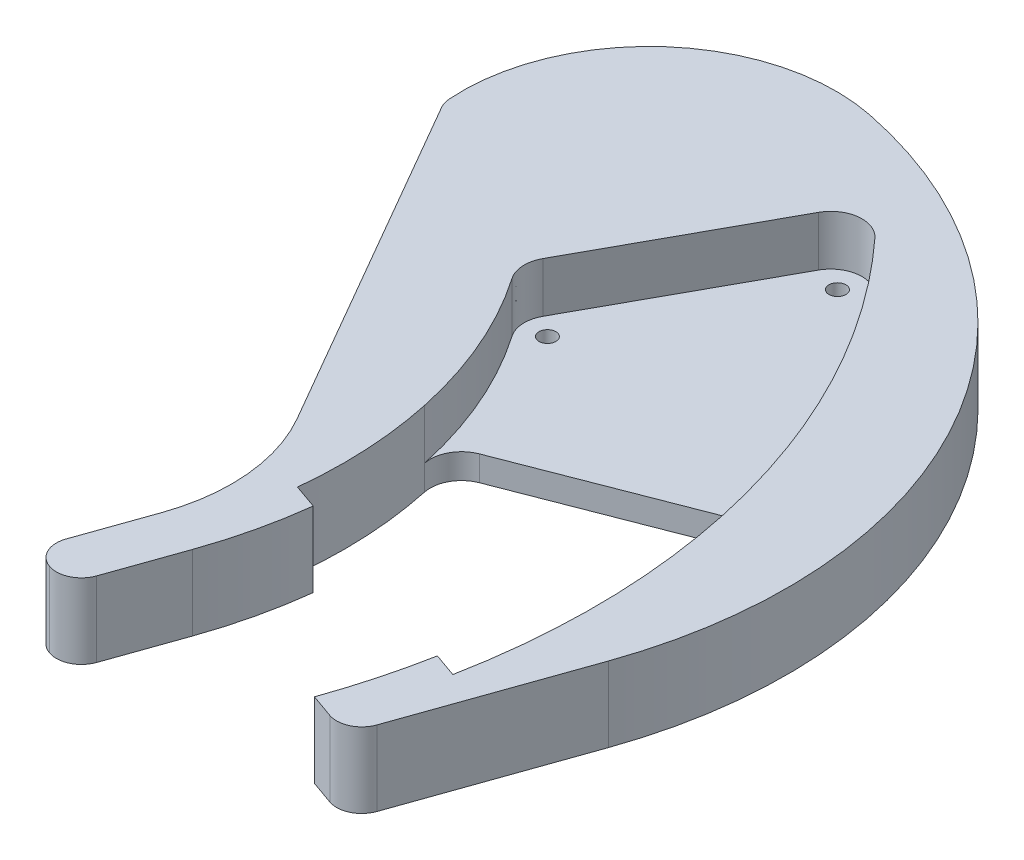
SolidWorks part; units mm, degrees
material "Pine"
ref_plane "Front Plane" through (0, 0, 0) normal (0, 0, 1) x (1, 0, 0)
ref_plane "Top Plane" through (0, 0, 0) normal (0, 1, 0) x (1, 0, 0)
ref_plane "Right Plane" through (0, 0, 0) normal (1, 0, 0) x (0, 0, -1)
sketch "Sketch1" plane through (0, 0, 0) normal (0, 1, 0) x (1, 0, 0)
  line L59 (-47.4532, 53.4043) -> (-98.2532, 141.3925)
  line L60 (0, 0) -> (27.9445, -9.8615)
  line L61 (0, 0) -> (-43.9505, 15.5099)
  line L62 (-1000, 0) -> (49000, 0) construction
  line L64 (27.9445, -9.8615) -> (72.8551, -25.7103) construction
  line L65 (72.8551, -25.7103) -> (88.7038, 19.2003) construction
  line L66 (27.9445, -9.8615) -> (-207.1917, -676.1663) construction
  line L67 (45.3803, 39.5461) -> (27.9445, -9.8615)
  line L68 (-43.9505, 15.5099) -> (-28.1017, 60.4205) construction
  line L69 (-88.861, 31.3587) -> (-86.5095, 38.0222) construction
  line L70 (53.7407, 188.0768) -> (-24.6782, 188.0768) construction
  line L71 (-43.9505, 15.5099) -> (-88.861, 31.3587) construction
  arc A0 (45.3803, 39.5461) -> (-41.5665, 192.8393) centre (-64.7226, 78.401) ccw
  arc A1 (-98.2532, 141.3925) -> (-41.5665, 192.8393) centre (-50.9898, 146.2689) cw
  arc A2 (-43.9505, 15.5099) -> (-47.4532, 53.4043) centre (-86.8603, 30.6526) ccw
  dimension "D5" = 4.7625
  dimension "D2" = 45.5033
  dimension "D11" = 37.8944
  dimension "D12" = 7.0663
  dimension "D8" = 52.3939
  dimension "D9" = 46.6069
  dimension "D4" = 19.438
  dimension "D7" = 116.7576
  dimension "D6" = 47.5143
  dimension "D10" = 29.6335
  dimension "D3" = 101.6
  dimension "D1" = 47.625
  dimension "D13" = 78.4189
extrude "Boss-Extrude1" add sketch "Sketch1" along normal blind 19.05
ref_plane "Plane1" through (-8.003, 0, -2.8242) normal (0.943, 0, 0.3328) x (0.3328, 0, -0.943)
sketch "Sketch2" plane through (0, 0, 0) normal (0, 1, 0) x (1, 0, 0)
  line L0 (-43.9505, 15.5099) -> (27.9445, -9.8615) construction
  point P2 (-8.003, 2.8242)
  point P3 (-8.003, 2.8242)
  line B0 (-29.2366, 81.4276) -> (15.5744, 98.7927)
  line B1 (11.6131, 92.147) -> (-21.6985, 79.2205)
  line B2 (-25.5648, 59.5252) -> (22.719, 42.4861)
  line B3 (28.6163, 16.8366) -> (22.5595, 18.974)
  line B4 (-26.1738, 36.1718) -> (-32.322, 38.3415)
  line B5 (-25.1489, 88.1192) -> (10.3796, 101.8872)
  line B6 (-51.3926, 119.7839) -> (-26.6046, 164.8774)
  line B7 (-44.0739, 123.2114) -> (-25.3, 157.3642)
  line B8 (-31.9553, 11.2769) -> (15.9493, -5.6285)
  line B9 (22.5595, 18.974) -> (-26.1738, 36.1718)
  arc B10 (-27.5994, 72.1341) -> (-28.8269, 77.6086) centre (-28.1238, 74.8914) ccw
  arc B11 (-29.2366, 81.4276) -> (-29.7842, 81.1914) centre (-26.3685, 74.0264) ccw
  arc B12 (17.8172, 99.3043) -> (15.5744, 98.7927) centre (18.4425, 91.3914) ccw
  arc B13 (18.8456, 95.8956) -> (20.3121, 90.5015) centre (19.3312, 93.1313) ccw
  arc B14 (13.6735, 91.1895) -> (20.9914, 87.3846) centre (19.3312, 93.1313) ccw
  arc B15 (-27.0229, 69.0118) -> (-22.587, 77.1552) centre (-28.1238, 74.8914) ccw
  arc B16 (20.3121, 90.5015) -> (18.8456, 95.8956) centre (19.3312, 93.1313) ccw
  arc B17 (28.6163, 16.8366) -> (26.1201, 93.4056) centre (-140.6727, 49.6428) ccw
  arc B18 (26.9496, 45.3998) -> (22.9664, 86.2145) centre (-140.6737, 49.643) ccw
  arc B19 (-28.827, 77.6085) -> (-27.5994, 72.1341) centre (-28.1238, 74.8914) ccw
  arc B20 (-27.6639, 62.1695) -> (-25.8173, 59.6267) centre (-24.5082, 62.5193) ccw
  arc B21 (-32.322, 38.3415) -> (-34.1314, 72.3702) centre (-140.6727, 49.6428) ccw
  arc B22 (10.3796, 101.8872) -> (14.8753, 112.2511) centre (7.5115, 109.2884) ccw
  arc B23 (-35.3684, 92.527) -> (-25.1489, 88.1192) centre (-28.017, 95.5204) ccw
  arc B24 (-43.0735, 110.8831) -> (-43.464, 121.0781) centre (-46.3902, 115.8611) ccw
  arc B25 (15.9493, -5.6285) -> (22.5595, 18.974) centre (-140.6729, 49.642) ccw
  arc B26 (-31.9553, 11.2769) -> (-26.1738, 36.1718) centre (-140.6725, 49.6436) ccw
  spline B27 degree 3 poles (17.8172, 99.3043) (18.2808, 99.3409) (18.7407, 99.3366) (19.6534, 99.2495) (20.1077, 99.1662) (21.0026, 98.9191) (21.4331, 98.7584) (22.0543, 98.4634) (22.2573, 98.356) (22.6549, 98.123) (22.8504, 97.9967) (23.4171, 97.5941) (23.7667, 97.2963) (24.2502, 96.807) (24.4045, 96.6367) (24.699, 96.2816) (24.84, 96.0958) (25.2347, 95.5249) (25.4616, 95.126) (25.8451, 94.2925) (26.0022, 93.8555) (26.1202, 93.4057) knots 0 0 0 0 0.125 0.125 0.25 0.25 0.375 0.375 0.4375 0.4375 0.5 0.5 0.625 0.625 0.6875 0.6875 0.75 0.75 0.875 0.875 1 1 1 1
  spline B28 degree 3 poles (-34.1313, 72.3702) (-34.3175, 73.2427) (-34.3554, 74.1214) (-34.1352, 75.8909) (-33.8828, 76.7344) (-33.0952, 78.3332) (-32.5797, 79.0482) (-31.6292, 79.9869) (-31.2886, 80.2706) (-30.5679, 80.7764) (-30.1868, 80.9994) (-29.7842, 81.1914) knots 0 0 0 0 0.25 0.25 0.5 0.5 0.75 0.75 0.875 0.875 1 1 1 1
  spline B29 degree 2 poles (-26.6046, 164.8774) (-26.1506, 165.7033) (-25.5154, 166.4003) (-24.879, 167.0987) (-24.0954, 167.6288) (-23.3138, 168.1575) (-22.4289, 168.4884) (-21.5475, 168.8181) (-20.6123, 168.9325) (-19.6749, 169.0473) (-18.7356, 168.9385) (-17.7973, 168.83) (-16.9097, 168.5037) (-16.0263, 168.179) (-15.2426, 167.656) (-14.4528, 167.129) (-13.8094, 166.4302) knots 0 0 0 0.125 0.125 0.25 0.25 0.375 0.375 0.5 0.5 0.625 0.625 0.75 0.75 0.875 0.875 1 1 1
  spline B30 degree 3 poles (26.1163, 93.4018) (24.3249, 100.238) (22.1302, 106.9013) (16.9621, 119.8936) (13.988, 126.2224) (9.777, 133.9217) (8.91, 135.4509) (7.1262, 138.488) (6.208, 139.9978) (3.3864, 144.4804) (1.4239, 147.3946) (-4.7015, 155.9203) (-9.1008, 161.3163) (-13.8094, 166.4302) knots 0 0 0 0 0.25 0.25 0.5 0.5 0.5625 0.5625 0.625 0.625 0.75 0.75 1 1 1 1
  spline B31 degree 3 poles (-13.3161, 158.7044) (-10.6959, 155.6457) (-8.187, 152.4937) (-4.3894, 147.3517) (-3.0295, 145.4278) (-0.3835, 141.5096) (0.9037, 139.513) (3.3926, 135.4673) (4.5925, 133.4211) (6.8969, 129.2936) (8.0024, 127.2107) (11.1817, 120.9021) (13.1195, 116.615) (14.8753, 112.2511) knots 0.074143 0.074143 0.074143 0.074143 0.222946 0.222946 0.309438 0.309438 0.395929 0.395929 0.48242 0.48242 0.568911 0.568911 0.741894 0.741894 0.741894 0.741894
  spline B32 degree 3 poles (-35.3684, 92.527) (-36.6307, 95.6269) (-38.0226, 98.6534) (-40.7885, 104.036) (-42.1249, 106.4194) (-43.5456, 108.7522) knots 0.447067 0.447067 0.447067 0.447067 0.670186 0.670186 0.854821 0.854821 0.854821 0.854821
  spline B33 degree 2 poles (-50.9715, 111.4537) (-51.5973, 112.3613) (-51.9523, 113.4056) (-52.3075, 114.4507) (-52.3641, 115.5542) (-52.4206, 116.6572) (-52.1734, 117.7348) (-51.9261, 118.8136) (-51.3926, 119.7839) knots 0 0 0 0.25 0.25 0.5 0.5 0.75 0.75 1 1 1
  spline B34 degree 3 poles (-50.9715, 111.4537) (-48.9588, 108.5346) (-47.0926, 105.5237) (-43.6539, 99.3178) (-42.0816, 96.1226) (-39.9504, 91.1875) (-39.2781, 89.5185) (-38.0214, 86.161) (-37.4355, 84.4688) (-36.3479, 81.058) (-35.8463, 79.3393) (-34.9276, 75.8754) (-34.5102, 74.1291) (-34.136, 72.3718) knots 0 0 0 0 0.25 0.25 0.5 0.5 0.625 0.625 0.75 0.75 0.875 0.875 1 1 1 1
sketch_block_instance "Ramp Geometry-1"
sketch_block "Ramp Geometry"
sketch "Sketch5" plane through (0, 19.05, 0) normal (0, 1, 0) x (1, 0, 0)
  line L1 (28.6163, 16.8366) -> (22.5595, 18.974) construction
  line L2 (-31.9553, 11.2769) -> (15.9493, -5.6285) construction
  line L3 (-26.1738, 36.1718) -> (-32.322, 38.3415) construction
  line L4 (-29.2366, 81.4276) -> (15.5744, 98.7927)
  line L5 (28.6163, 16.8366) -> (22.5595, 18.974)
  line L6 (-31.9553, 11.2769) -> (15.9493, -5.6285)
  line L7 (-26.1738, 36.1718) -> (-32.322, 38.3415)
  arc A2 (28.6163, 16.8366) -> (26.1201, 93.4056) centre (-140.6727, 49.6428) ccw construction
  arc A3 (15.9493, -5.6285) -> (22.5595, 18.974) centre (-140.6729, 49.642) ccw construction
  arc A4 (-31.9553, 11.2769) -> (-26.1738, 36.1718) centre (-140.6725, 49.6436) ccw construction
  arc A5 (-32.322, 38.3415) -> (-34.1314, 72.3702) centre (-140.6727, 49.6428) ccw construction
  arc A6 (-34.1314, 72.3702) -> (-29.2366, 81.4276) centre (-26.3759, 74.0303) cw
  arc A7 (26.1201, 93.4056) -> (15.5744, 98.7927) centre (18.4429, 91.3925) ccw
  arc A8 (28.6163, 16.8366) -> (26.1201, 93.4056) centre (-140.6727, 49.6428) ccw
  arc A9 (15.9493, -5.6285) -> (22.5595, 18.974) centre (-140.6729, 49.642) ccw
  arc A10 (-31.9553, 11.2769) -> (-26.1738, 36.1718) centre (-140.6725, 49.6436) ccw
  arc A11 (-32.322, 38.3415) -> (-34.1314, 72.3702) centre (-140.6727, 49.6428) ccw
  spline S2 degree 3 poles (17.8172, 99.3043) (18.2808, 99.3409) (18.7407, 99.3366) (19.6534, 99.2495) (20.1077, 99.1662) (21.0026, 98.9191) (21.4331, 98.7584) (22.0543, 98.4634) (22.2573, 98.356) (22.6549, 98.123) (22.8504, 97.9967) (23.4171, 97.5941) (23.7667, 97.2963) (24.2502, 96.807) (24.4045, 96.6367) (24.699, 96.2816) (24.84, 96.0958) (25.2347, 95.5249) (25.4616, 95.126) (25.8451, 94.2925) (26.0022, 93.8555) (26.1202, 93.4057) knots 0 0 0 0 0.125 0.125 0.25 0.25 0.375 0.375 0.4375 0.4375 0.5 0.5 0.625 0.625 0.6875 0.6875 0.75 0.75 0.875 0.875 1 1 1 1 construction
  spline S3 degree 3 poles (-34.1313, 72.3702) (-34.3175, 73.2427) (-34.3554, 74.1214) (-34.1352, 75.8909) (-33.8828, 76.7344) (-33.0952, 78.3332) (-32.5797, 79.0482) (-31.6292, 79.9869) (-31.2886, 80.2706) (-30.5679, 80.7764) (-30.1868, 80.9994) (-29.7842, 81.1914) knots 0 0 0 0 0.25 0.25 0.5 0.5 0.75 0.75 0.875 0.875 1 1 1 1 construction
extrude "Cut-Extrude1" cut sketch "Sketch5" against normal through all
sketch "Sketch6" plane through (0, 19.05, 0) normal (0, 1, 0) x (1, 0, 0)
  line L0 (-34.136, 72.3718) -> (26.1163, 93.4018)
  line L2 (-51.3926, 119.7839) -> (-26.6046, 164.8774) construction
  line L3 (-51.3926, 119.7839) -> (-26.6046, 164.8774)
  spline S0 degree 3 poles (-1429.6439, -1247.1312) (-221.2393, -482.3872) (103.2117, -96.9361) (16.9621, 119.8936) (13.988, 126.2224) (9.777, 133.9217) (8.91, 135.4509) (7.1262, 138.488) (6.208, 139.9978) (3.3864, 144.4804) (1.4239, 147.3946) (-186.5695, 409.0534) (-1027.0588, 71.2021) (-1932.3264, -325.7002) knots -7.844512 -7.844512 -7.844512 -7.844512 0.25 0.25 0.5 0.5 0.5625 0.5625 0.625 0.625 0.75 0.75 12.134027 12.134027 12.134027 12.134027 only from (26.1163, 93.4018) to (-13.8094, 166.4302) construction
  spline S1 degree 2 poles (1493.7423, -1132.5068) (-85.9486, 100.0778) (-25.5154, 166.4003) (-24.879, 167.0987) (-24.0954, 167.6288) (-23.3138, 168.1575) (-22.4289, 168.4884) (-21.5475, 168.8181) (-20.6123, 168.9325) (-19.6749, 169.0473) (-18.7356, 168.9385) (-17.7973, 168.83) (-16.9097, 168.5037) (-16.0263, 168.179) (-15.2426, 167.656) (59.3198, 117.902) (-1170.3473, -1463.6448) knots -11.768568 -11.768568 -11.768568 0.125 0.125 0.25 0.25 0.375 0.375 0.5 0.5 0.625 0.625 0.75 0.75 0.875 0.875 12.67723 12.67723 12.67723 only from (-26.6046, 164.8774) to (-13.8094, 166.4302) construction
  spline S2 degree 2 poles (1805.4899, 851.8486) (-23.0142, 28.2719) (-51.9523, 113.4056) (-52.3075, 114.4507) (-52.3641, 115.5542) (-52.4206, 116.6572) (-52.1734, 117.7348) (-32.0934, 205.297) (1872.6772, -421.0496) knots -20.129916 -20.129916 -20.129916 0.25 0.25 0.5 0.5 0.75 0.75 21.042954 21.042954 21.042954 only from (-50.9715, 111.4537) to (-51.3926, 119.7839) construction
  spline S3 degree 3 poles (-1984.765, -331.989) (-829.3418, 131.8338) (-152.4686, 295.6978) (-43.6539, 99.3178) (-42.0816, 96.1226) (-39.9504, 91.1875) (-39.2781, 89.5185) (-38.0214, 86.161) (-37.4355, 84.4688) (-36.3479, 81.058) (-35.8463, 79.3393) (3.3124, -68.2971) (-256.1389, -315.9435) (-1530.5486, 1352.6355) knots -15.321981 -15.321981 -15.321981 -15.321981 0.25 0.25 0.5 0.5 0.625 0.625 0.75 0.75 0.875 0.875 11.405236 11.405236 11.405236 11.405236 only from (-50.9715, 111.4537) to (-34.136, 72.3718) construction
  spline S4 degree 3 poles (26.1163, 93.4018) (24.3249, 100.238) (22.1302, 106.9013) (16.9621, 119.8936) (13.988, 126.2224) (9.777, 133.9217) (8.91, 135.4509) (7.1262, 138.488) (6.208, 139.9978) (3.3864, 144.4804) (1.4239, 147.3946) (-4.7015, 155.9203) (-9.1008, 161.3163) (-13.8094, 166.4302) knots 0 0 0 0 0.25 0.25 0.5 0.5 0.5625 0.5625 0.625 0.625 0.75 0.75 1 1 1 1
  spline S5 degree 2 poles (-26.6046, 164.8774) (-26.1506, 165.7033) (-25.5154, 166.4003) (-24.879, 167.0987) (-24.0954, 167.6288) (-23.3138, 168.1575) (-22.4289, 168.4884) (-21.5475, 168.8181) (-20.6123, 168.9325) (-19.6749, 169.0473) (-18.7356, 168.9385) (-17.7973, 168.83) (-16.9097, 168.5037) (-16.0263, 168.179) (-15.2426, 167.656) (-14.4528, 167.129) (-13.8094, 166.4302) knots 0 0 0 0.125 0.125 0.25 0.25 0.375 0.375 0.5 0.5 0.625 0.625 0.75 0.75 0.875 0.875 1 1 1
  spline S6 degree 2 poles (-50.9715, 111.4537) (-51.5973, 112.3613) (-51.9523, 113.4056) (-52.3075, 114.4507) (-52.3641, 115.5542) (-52.4206, 116.6572) (-52.1734, 117.7348) (-51.9261, 118.8136) (-51.3926, 119.7839) knots 0 0 0 0.25 0.25 0.5 0.5 0.75 0.75 1 1 1
  spline S7 degree 3 poles (-50.9715, 111.4537) (-48.9588, 108.5346) (-47.0926, 105.5237) (-43.6539, 99.3178) (-42.0816, 96.1226) (-39.9504, 91.1875) (-39.2781, 89.5185) (-38.0214, 86.161) (-37.4355, 84.4688) (-36.3479, 81.058) (-35.8463, 79.3393) (-34.9276, 75.8754) (-34.5102, 74.1291) (-34.136, 72.3718) knots 0 0 0 0 0.25 0.25 0.5 0.5 0.625 0.625 0.75 0.75 0.875 0.875 1 1 1 1
extrude "Cut-Extrude2" cut sketch "Sketch6" against normal blind 12.7
sketch "Sketch7" plane through (0, 0, 0) normal (0, 1, 0) x (1, 0, 0)
  line L0 (-43.9505, 15.5099) -> (-52.4031, -8.4424)
  line L1 (-52.4031, -8.4424) -> (-40.4081, -12.6754)
  line L2 (-40.4081, -12.6754) -> (-31.9553, 11.2769)
  line L3 (-31.9553, 11.2769) -> (-43.9505, 15.5099)
  arc A0 (-31.9553, 11.2769) -> (-26.1738, 36.1718) centre (-140.6725, 49.6436) ccw construction
  arc A1 (-43.9505, 15.5099) -> (-47.4532, 53.4043) centre (-86.8603, 30.6526) ccw construction
  dimension "D1" = 25.4
extrude "Boss-Extrude2" add sketch "Sketch7" along normal up to surface (19.05 mm away) up to face at (-15.4124, 19.05, -73.243)
fillet "Fillet1" radius 6.35 4 edges at (-98.2532, 9.525, -141.3925) (27.9445, 9.525, 9.8615) (-40.4081, 9.525, 12.6754) (-52.4031, 9.525, 8.4424)
hole_wizard "#8 Clearance Hole1" positions "Sketch8" profile "Sketch9" hole size "#8" standard "ANSI Inch" end condition through all
sketch "Sketch8" plane through (0, 0, 0) normal (0, -1, 0) x (-1, 0, 0)
  line L0 (46.3904, 115.861) -> (19.8844, 162.9953) construction
  line L2 (19.8844, 162.9953) -> (13.8094, 166.4302) construction
  line L5 (46.3904, 115.861) -> (50.9715, 111.4537) construction
  spline S0 degree 2 poles (13.8094, 166.4302) (14.4528, 167.129) (15.2426, 167.656) (16.0263, 168.179) (16.9097, 168.5037) (17.7973, 168.83) (18.7356, 168.9385) (19.6749, 169.0473) (20.6123, 168.9325) (21.5475, 168.8181) (22.4289, 168.4884) (23.3138, 168.1575) (24.0954, 167.6288) (24.879, 167.0987) (25.5154, 166.4003) (26.1506, 165.7033) (26.6046, 164.8774) knots 0 0 0 0.125 0.125 0.25 0.25 0.375 0.375 0.5 0.5 0.625 0.625 0.75 0.75 0.875 0.875 1 1 1 construction
  spline S1 degree 3 poles (-26.0451, 93.6725) (-24.2669, 100.414) (-22.096, 106.987) (-16.9621, 119.8936) (-13.988, 126.2224) (-9.777, 133.9217) (-8.91, 135.4509) (-7.1262, 138.488) (-6.208, 139.9978) (-3.3864, 144.4804) (-1.4239, 147.3946) (4.7015, 155.9203) (9.1008, 161.3163) (13.8094, 166.4302) knots 0.003301 0.003301 0.003301 0.003301 0.25 0.25 0.5 0.5 0.5625 0.5625 0.625 0.625 0.75 0.75 1 1 1 1 construction
  spline S2 degree 2 poles (51.3926, 119.7839) (51.9261, 118.8136) (52.1734, 117.7348) (52.4206, 116.6572) (52.3641, 115.5542) (52.3075, 114.4507) (51.9523, 113.4056) (51.5973, 112.3613) (50.9715, 111.4537) knots 0 0 0 0.25 0.25 0.5 0.5 0.75 0.75 1 1 1 construction
  point P0 (46.3904, 115.861)
  point P2 (19.8844, 162.9953)
  dimension "D1" = 54.0759
  dimension "D2" = 6.357
  dimension "D3" = 6.9788
  dimension "D4" = 148.836
  dimension "D5" = 163.244
sketch "Sketch9" plane through (-46.3904, 0, -115.861) normal (1, 0, 0) x (0, 0, -1)
  line L0 (0, 0) -> (0, 19.05)
  line L1 (0, 19.05) -> (2.1526, 19.05)
  line L2 (2.1526, 19.05) -> (2.1526, 0)
  line L5 (2.1526, 0) -> (0, 0)
  line L11 (0, -6.35) -> (0, 107.95) construction
  dimension "Thru Hole Dia." = 4.3053
  dimension "Thru Hole Depth" = 19.05
sketch "Sketch10" plane through (0, 0, 0) normal (0, -1, 0) x (1, 0, 0)
  line L0 (54.184, -189.0962) -> (-27.589, -189.0962)
  arc A0 (-41.5665, -192.8393) -> (45.3803, -39.5461) centre (-64.7226, -78.401) ccw construction
  point P3 (0, 0)
  point P7 (0, 0)
  dimension "D1" = 81.773
  dimension "D2" = 189.0962
